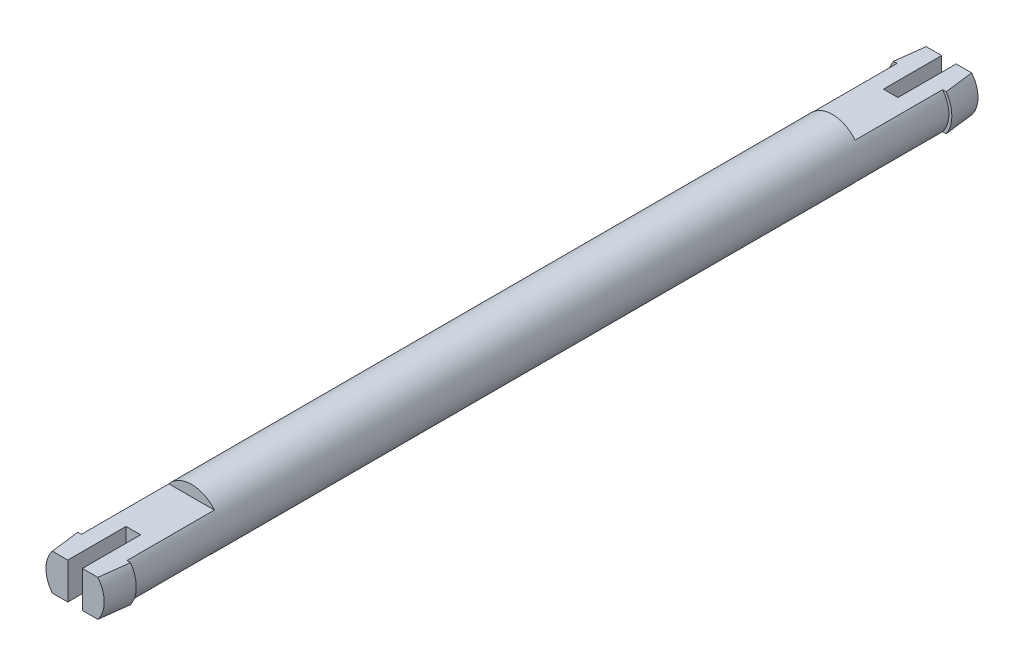
SolidWorks part; units mm, degrees
ref_plane "前视基准面" through (0, 0, 0) normal (0, 0, 1) x (1, 0, 0)
ref_plane "上视基准面" through (0, 0, 0) normal (0, 1, 0) x (1, 0, 0)
ref_plane "右视基准面" through (0, 0, 0) normal (1, 0, 0) x (0, 0, -1)
sketch "草图1" plane through (0, 0, 0) normal (0, 0, 1) x (1, 0, 0)
  circle A0 centre (0, 0) radius 2
extrude "凸台-拉伸1" add sketch "草图1" against normal blind 60
sketch "草图2" plane through (0, 0, 0) normal (0, 1, 0) x (1, 0, 0)
  line L0 (0, 0) -> (0, 2)
  line L1 (0, 2) -> (2.2, 2)
  line L2 (0, 0) -> (2, 0)
  line L3 (2, 0) -> (2.2, 2)
  dimension "D1" = 2.2
  dimension "D2" = 2
revolve "旋转1" add sketch "草图2" angle 360 about L0
sketch "草图3" plane through (0, 0, 0) normal (0, 0, 1) x (1, 0, 0)
  line L0 (-2.1, 1.25) -> (-2.1, 2.25)
  line L1 (-2.1, 1.25) -> (2.1, 1.25)
  line L2 (2.1, 1.25) -> (2.1, 2.25)
  line L3 (-2.1, -1.25) -> (2.1, -1.25)
  line L5 (-2.1, -2.25) -> (2.1, -2.25)
  line L6 (-2.1, -2.25) -> (-2.1, -1.25)
  line L7 (-2.1, 2.25) -> (2.1, 2.25)
  line L8 (2.1, -2.25) -> (2.1, -1.25)
  dimension "D1" = 1.25
  dimension "D2" = 1.25
  dimension "D3" = 1
  dimension "D4" = 1
extrude "切除-拉伸1" cut sketch "草图3" against normal blind 8
sketch "草图4" plane through (0, -1.25, 0) normal (0, -1, 0) x (1, 0, 0)
  line L0 (1.5612, 0) -> (-1.5612, 0) construction
  line L1 (-0.5, 0) -> (0.5, 0)
  line L2 (-0.5, 0) -> (-0.5, -4)
  line L3 (-0.5, -4) -> (0.5, -4)
  line L4 (0.5, 0) -> (0.5, -4)
extrude "切除-拉伸2" cut sketch "草图4" against normal up to next
sketch "草图5" plane through (0, 0, 0) normal (0, 1, 0) x (1, 0, 0)
  line L0 (0, 60) -> (0, 58)
  line L1 (2, 60) -> (-2, 60) construction
  line L2 (0, 58) -> (2.2, 58)
  line L3 (2.2, 58) -> (2, 60)
  line L4 (2, 60) -> (0, 60)
  line L5 (0, 58.1377) -> (0, 60.3241) construction
  dimension "D1" = 2.2
  dimension "D2" = 2
revolve "旋转2" add sketch "草图5" angle 360 about L5
sketch "草图6" plane through (0, 0, -60) normal (0, 0, -1) x (-1, 0, 0)
  line L1 (-2.1, 1.25) -> (2.1, 1.25)
  line L2 (-2.1, 1.25) -> (-2.1, 2.25)
  line L3 (-2.1, 2.25) -> (2.1, 2.25)
  line L4 (2.1, 1.25) -> (2.1, 2.25)
  line L5 (-2.1, -1.25) -> (2.1, -1.25)
  line L6 (-2.1, -1.25) -> (-2.1, -2.25)
  line L7 (-2.1, -2.25) -> (2.1, -2.25)
  line L8 (2.1, -1.25) -> (2.1, -2.25)
  dimension "D1" = 1.25
  dimension "D2" = 1.25
  dimension "D3" = 1
  dimension "D4" = 1
extrude "切除-拉伸3" cut sketch "草图6" against normal blind 8
sketch "草图7" plane through (0, 0, 0) normal (0, 1, 0) x (1, 0, 0)
  line L0 (1.5612, 60) -> (-1.5612, 60) construction
  line L1 (-0.5, 60) -> (0.5, 60)
  line L2 (-0.5, 60) -> (-0.5, 56)
  line L3 (-0.5, 56) -> (0.5, 56)
  line L4 (0.5, 60) -> (0.5, 56)
extrude "切除-拉伸4" cut sketch "草图7" against normal through all and the other way through all
